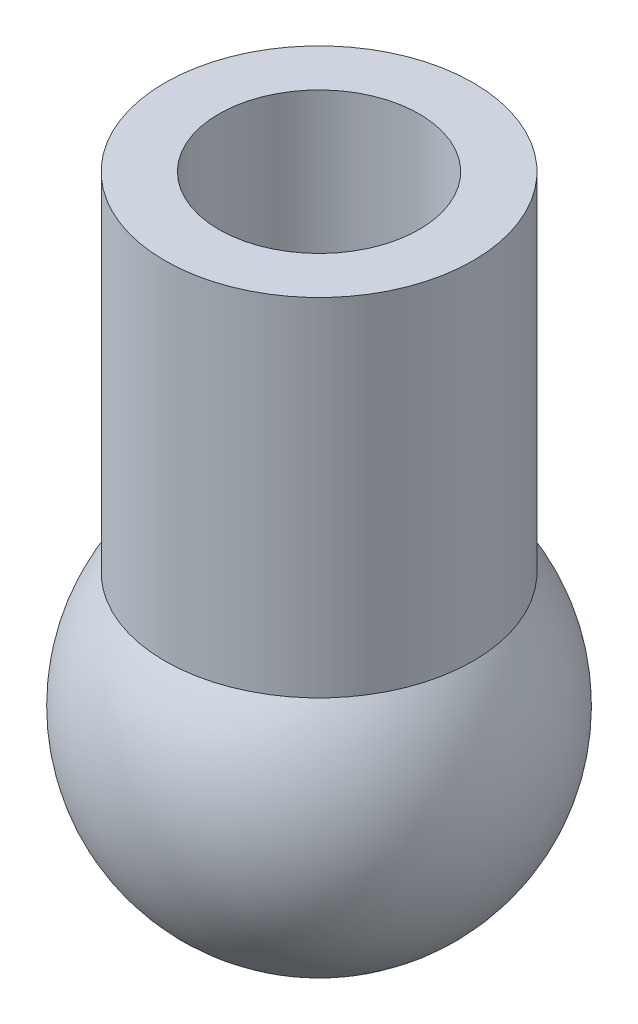
SolidWorks part; units mm, degrees
ref_plane "Front Plane" through (0, 0, 0) normal (0, 0, 1) x (1, 0, 0)
ref_plane "Top Plane" through (0, 0, 0) normal (0, 1, 0) x (1, 0, 0)
ref_plane "Right Plane" through (0, 0, 0) normal (1, 0, 0) x (0, 0, -1)
sketch "Sketch1" plane through (0, 0, 0) normal (0, 0, 1) x (1, 0, 0)
  line L2 (4.6643, 0) -> (-6.7323, 0) construction
  line L3 (-2.5, 0) -> (2.5, 0)
  arc A0 (-2.5, 0) -> (2.5, 0) centre (0, 0) ccw
  dimension "D1" = 5
revolve "Revolve2" add sketch "Sketch1" angle 360 about L2
sketch "Sketch2" plane through (0, 0, 0) normal (0, 1, 0) x (1, 0, 0)
  circle A0 centre (0, 0) radius 1.3
  dimension "D1" = 2.6
extrude "Cut-Extrude1" cut sketch "Sketch2" against normal mid plane 30
sketch "Sketch3" plane through (0, 0, 0) normal (0, 1, 0) x (1, 0, 0)
  circle A0 centre (0, 0) radius 2
  circle A1 centre (0, 0) radius 1.3
  dimension "D1" = 2.6
  dimension "D2" = 4
extrude "Boss-Extrude1" add sketch "Sketch3" along normal blind 6
